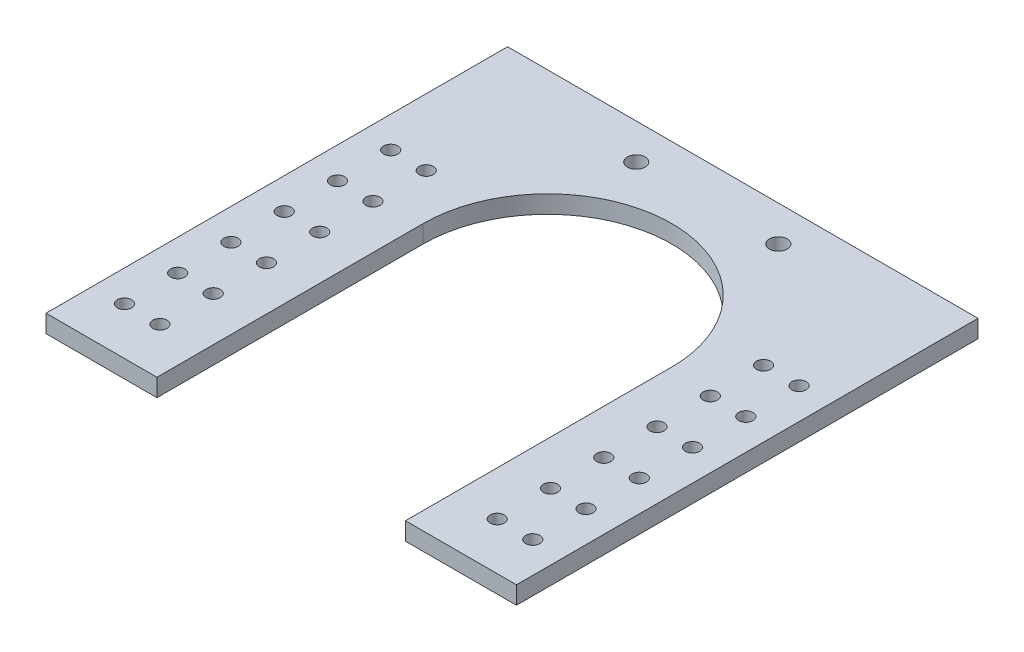
SolidWorks part; units mm, degrees
ref_plane "Front" through (0, 0, 0) normal (0, 0, 1) x (1, 0, 0)
ref_plane "Top" through (0, 0, 0) normal (0, 1, 0) x (1, 0, 0)
ref_plane "Right" through (0, 0, 0) normal (1, 0, 0) x (0, 0, -1)
sketch "Sketch1" plane through (0, 0, 0) normal (0, 1, 0) x (1, 0, 0)
  line L1 (-84.1375, -82.55) -> (84.1375, -82.55)
  line L2 (-84.1375, -82.55) -> (-84.1375, 82.55)
  line L3 (-84.1375, 82.55) -> (84.1375, 82.55)
  line L4 (84.1375, -82.55) -> (84.1375, 82.55)
  line L5 (-84.1375, -82.55) -> (84.1375, 82.55) construction
  line L6 (-84.1375, 82.55) -> (84.1375, -82.55) construction
  point P0 (0, 0)
  dimension "D1" = 168.275
  dimension "D2" = 165.1
extrude "Boss-Extrude1" add sketch "Sketch1" along normal mid plane 6.35 contours L3 L4 L1 L2
sketch "Sketch2" plane through (0, 3.175, 0) normal (0, 1, 0) x (1, 0, 0)
  line L0 (0, -50) -> (0, 50) construction
  line L1 (-84.1375, 82.55) -> (84.1375, 82.55) construction
  line L2 (44.45, 12.7) -> (44.45, -82.55)
  line L3 (-84.1375, -82.55) -> (84.1375, -82.55) construction
  line L4 (44.45, -82.55) -> (-44.45, -82.55)
  line L5 (-44.45, -82.55) -> (-44.45, 12.7)
  circle A0 centre (0, 12.7) radius 44.45
  point P4 (0, 57.15)
  line M2 (-84.1375, -82.55) -> (84.1375, -82.55)
  dimension "D2" = 88.9
  dimension "D1" = 25.4
extrude "Cut-Extrude1" cut sketch "Sketch2" against normal up to next contours A0 | A0 L5 L2 M2
sketch "Sketch3" plane through (0, 3.175, 0) normal (0, 1, 0) x (1, 0, 0)
  line L0 (-25.4, 69.85) -> (25.4, 69.85) construction
  line L1 (0, -50) -> (0, 50) construction
  line L2 (-84.1375, 82.55) -> (84.1375, 82.55) construction
  point P0 (-25.4, 69.85)
  point P1 (25.4, 69.85)
  point P4 (0, 69.85)
  dimension "D1" = 50.8
  dimension "D2" = 12.7
hole_wizard "1/4 (0.25) Diameter Hole1" positions "Sketch4" profile "Sketch6" hole size "1/4" standard "ANSI Inch"
sketch "Sketch4" plane through (0, 3.175, 0) normal (0, 1, 0) x (1, 0, 0)
  point P0 (-25.4, 69.85)
  point P3 (25.4, 69.85)
sketch "Sketch6" plane through (-25.4, 3.175, -69.85) normal (1, 0, 0) x (0, 0, 1)
  line L0 (0, 0) -> (0, 27.3077)
  line L1 (0, 27.3077) -> (3.175, 25.4)
  line L2 (3.175, 25.4) -> (3.175, 0)
  line L5 (3.175, 0) -> (0, 0)
  line L10 (0, 27.3077) -> (-3.175, 25.4) construction
  line L11 (0, -6.35) -> (0, 107.95) construction
  dimension "Hole Dia." = 6.35
  dimension "Hole Depth" = 25.4
  dimension "Drill Angle" = 118
sketch "Sketch7" plane through (0, 3.175, 0) normal (0, 1, 0) x (1, 0, 0)
  line L0 (-84.1375, -82.55) -> (-84.1375, 82.55) construction
  point P0 (-73.025, -65.6037)
  point P1 (-60.325, -65.6037)
  point P2 (0, 0)
  dimension "D1" = 11.1125
  dimension "D2" = 12.7
hole_wizard "1/4-20 Tapped Hole1" positions "Sketch8" profile "Sketch10" tap size "1/4-20" standard "ANSI Inch"
sketch "Sketch8" plane through (0, 3.175, 0) normal (0, 1, 0) x (1, 0, 0)
  point P0 (-73.025, -65.6037)
  point P3 (-60.325, -65.6037)
sketch "Sketch10" plane through (-73.025, 3.175, 65.6037) normal (1, 0, 0) x (0, 0, 1)
  line L0 (0, 0) -> (0, 26.9338)
  line L1 (0, 26.9338) -> (2.5527, 25.4)
  line L2 (2.5527, 25.4) -> (2.5527, 0)
  line L5 (2.5527, 0) -> (0, 0)
  line L10 (0, 26.9338) -> (-2.5527, 25.4) construction
  line L11 (0, -6.35) -> (0, 107.95) construction
  dimension "Tap Drill Dia." = 5.1054
  dimension "Tap Drill Depth" = 25.4
  dimension "Drill Angle" = 118
cosmetic thread "Hole Thread1" parameters "D1"=12.7, "D2"=6.35
cosmetic thread "Hole Thread2" parameters "D1"=12.7, "D2"=6.35
pattern_linear "LPattern1" count 6 spacing 19.05 along (0, 0, -1) of "1/4-20 Tapped Hole1"
cosmetic thread "Hole Thread3" parameters "D1"=12.7, "D2"=6.35
cosmetic thread "Hole Thread4" parameters "D1"=12.7, "D2"=6.35
cosmetic thread "Hole Thread5" parameters "D1"=12.7, "D2"=6.35
cosmetic thread "Hole Thread6" parameters "D1"=12.7, "D2"=6.35
cosmetic thread "Hole Thread7" parameters "D1"=12.7, "D2"=6.35
cosmetic thread "Hole Thread8" parameters "D1"=12.7, "D2"=6.35
cosmetic thread "Hole Thread9" parameters "D1"=12.7, "D2"=6.35
cosmetic thread "Hole Thread10" parameters "D1"=12.7, "D2"=6.35
cosmetic thread "Hole Thread11" parameters "D1"=12.7, "D2"=6.35
cosmetic thread "Hole Thread12" parameters "D1"=12.7, "D2"=6.35
mirror "Mirror1" about plane through (0, 0, 0) normal (1, 0, 0) of "LPattern1", "1/4-20 Tapped Hole1"
cosmetic thread "Hole Thread13" parameters "D1"=12.7, "D2"=6.35
cosmetic thread "Hole Thread14" parameters "D1"=12.7, "D2"=6.35
cosmetic thread "Hole Thread15" parameters "D1"=12.7, "D2"=6.35
cosmetic thread "Hole Thread16" parameters "D1"=12.7, "D2"=6.35
cosmetic thread "Hole Thread17" parameters "D1"=12.7, "D2"=6.35
cosmetic thread "Hole Thread18" parameters "D1"=12.7, "D2"=6.35
cosmetic thread "Hole Thread19" parameters "D1"=12.7, "D2"=6.35
cosmetic thread "Hole Thread20" parameters "D1"=12.7, "D2"=6.35
cosmetic thread "Hole Thread21" parameters "D1"=12.7, "D2"=6.35
cosmetic thread "Hole Thread22" parameters "D1"=12.7, "D2"=6.35
cosmetic thread "Hole Thread23" parameters "D1"=12.7, "D2"=6.35
cosmetic thread "Hole Thread24" parameters "D1"=12.7, "D2"=6.35
